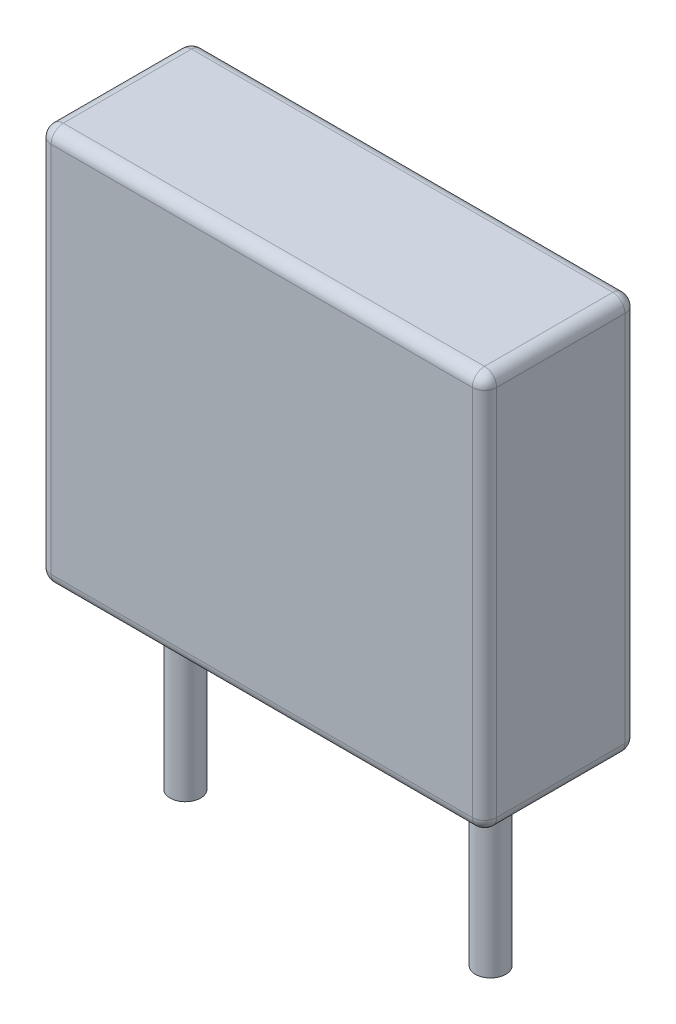
SolidWorks part; units mm, degrees
ref_plane "Front Plane" through (0, 0, 0) normal (0, 0, 1) x (1, 0, 0)
ref_plane "Top Plane" through (0, 0, 0) normal (0, 1, 0) x (1, 0, 0)
ref_plane "Right Plane" through (0, 0, 0) normal (1, 0, 0) x (0, 0, -1)
sketch "Sketch1" plane through (0, 0, 0) normal (0, 1, 0) x (1, 0, 0)
  line L1 (3.65, -1.25) -> (-3.65, -1.25)
  line L2 (3.65, -1.25) -> (3.65, 1.25)
  line L3 (3.65, 1.25) -> (-3.65, 1.25)
  line L4 (-3.65, -1.25) -> (-3.65, 1.25)
  line L5 (3.65, -1.25) -> (-3.65, 1.25) construction
  line L6 (3.65, 1.25) -> (-3.65, -1.25) construction
  point P0 (0, 0)
  dimension "D1" = 7.3
  dimension "D2" = 2.5
extrude "Boss-Extrude1" add sketch "Sketch1" along normal blind 6.5
sketch "Sketch2" plane through (0, 0, 0) normal (0, 1, 0) x (1, 0, 0)
  line L0 (2.5, 0) -> (-2.5, 0) construction
  circle A0 centre (-2.5, 0) radius 0.25
  circle A1 centre (2.5, 0) radius 0.25
  point P4 (0, 0)
  dimension "D1" = 0.5
  dimension "D2" = 5
extrude "Boss-Extrude2" add sketch "Sketch2" against normal blind 3 separate body
fillet "Fillet1" radius 0.2 12 edges at (-3.65, 0, 0) (-3.65, 3.25, -1.25) (0, 0, -1.25) (3.65, 3.25, -1.25) (3.65, 0, 0) (-3.65, 3.25, 1.25) (3.65, 3.25, 1.25) (0, 0, 1.25) (0, 6.5, -1.25) (3.65, 6.5, 0) (0, 6.5, 1.25) (-3.65, 6.5, 0)
